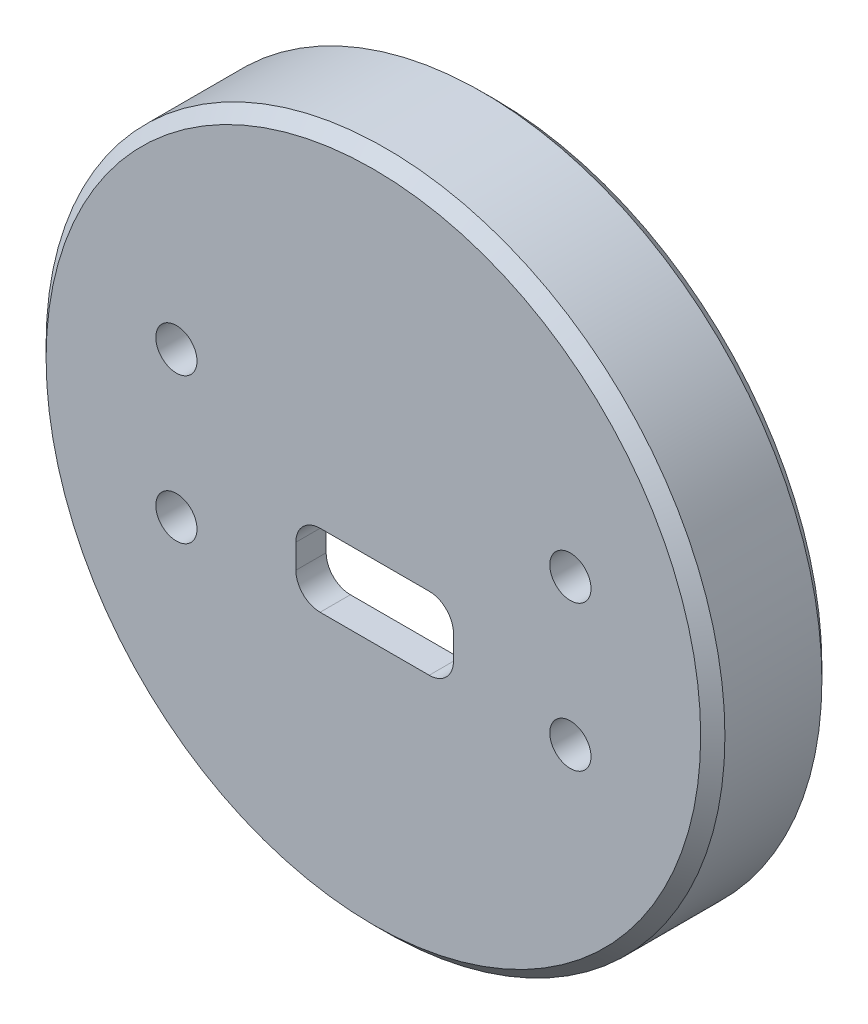
SolidWorks part; units mm, degrees
material "Сплав 2024"
ref_plane "Спереди" through (0, 0, 0) normal (0, 0, 1) x (1, 0, 0)
ref_plane "Сверху" through (0, 0, 0) normal (0, 1, 0) x (1, 0, 0)
ref_plane "Справа" through (0, 0, 0) normal (1, 0, 0) x (0, 0, -1)
sketch "Эскиз1" plane through (0, 0, 0) normal (0, 0, 1) x (1, 0, 0)
  circle A0 centre (0, 0) radius 28
  dimension "D1" = 56
extrude "Бобышка-Вытянуть1" add sketch "Эскиз1" along normal blind 10
sketch "Эскиз3" plane through (0, 0, 0) normal (0, 0, -1) x (-1, 0, 0)
  circle A0 centre (0, 0) radius 25
  dimension "D1" = 50
extrude "Вырез-Вытянуть2" cut sketch "Эскиз3" against normal offset from surface (7.5 mm away) 2.5 up to face at (28, 0, 10)
sketch "Эскиз6" plane through (0, 0, 7.5) normal (0, 0, -1) x (-1, 0, 0)
  line L1 (-6.6034, -0.86) -> (6.3966, -0.86)
  line L2 (-6.6034, -0.86) -> (-6.6034, -6.86)
  line L3 (-6.6034, -6.86) -> (6.3966, -6.86)
  line L4 (6.3966, -0.86) -> (6.3966, -6.86)
  line L5 (-6.6034, -0.86) -> (6.3966, -6.86) construction
  line L6 (-6.6034, -6.86) -> (6.3966, -0.86) construction
  point P0 (-0.1034, -3.86)
  dimension "D1" = 6
  dimension "D2" = 13
extrude "Вырез-Вытянуть4" cut sketch "Эскиз6" against normal up to next
fillet "Скругление3" radius 2 4 edges at (-6.3966, -0.86, 8.75) (-6.3966, -6.86, 8.75) (6.6034, -6.86, 8.75) (6.6034, -0.86, 8.75)
sketch "Эскиз7" plane through (0, 0, 7.5) normal (0, 0, -1) x (-1, 0, 0)
  line L0 (-22.25, -6) -> (18.9231, -6) construction
  line L1 (-22.25, -10) -> (-22.25, 10) construction
  line L2 (-22.25, 6) -> (18.9231, 6) construction
  line L5 (-16.25, -6) -> (-16.25, 6) construction
  line L6 (16.25, -6) -> (16.25, 6) construction
  dimension "D1" = 6
  dimension "D3" = 16.25
  dimension "D4" = 16.25
  dimension "D5" = 6
hole_wizard "Отверстие с зазором M31" positions "Эскиз9" profile "Эскиз8" hole size "M3" standard "Ansi Metric" end condition up to next
sketch "Эскиз9" plane through (0, 0, 7.5) normal (0, 0, -1) x (-1, 0, 0)
  point P0 (16.25, -6)
  point P3 (16.25, 6)
  point P6 (-16.25, 6)
  point P9 (-16.25, -6)
sketch "Эскиз8" plane through (-16.25, -6, 7.5) normal (1, 0, 0) x (0, 1, 0)
  line L0 (0, 0) -> (0, 2.5)
  line L1 (0, 2.5) -> (1.7, 2.5)
  line L2 (1.7, 2.5) -> (1.7, 0)
  line L5 (1.7, 0) -> (0, 0)
  line L11 (0, -6.35) -> (0, 107.95) construction
  dimension "Диаметр сквозного отверстия" = 3.4
  dimension "Глубина сквозного отверстия" = 2.5
ref_plane "Плоскость2" through (28, 0, 0) normal (1, 0, 0) x (0, 0, -1)
chamfer "Фаска1" distance 1 angle 45 2 edges at (28, 0, 10) (28, 0, 0)
